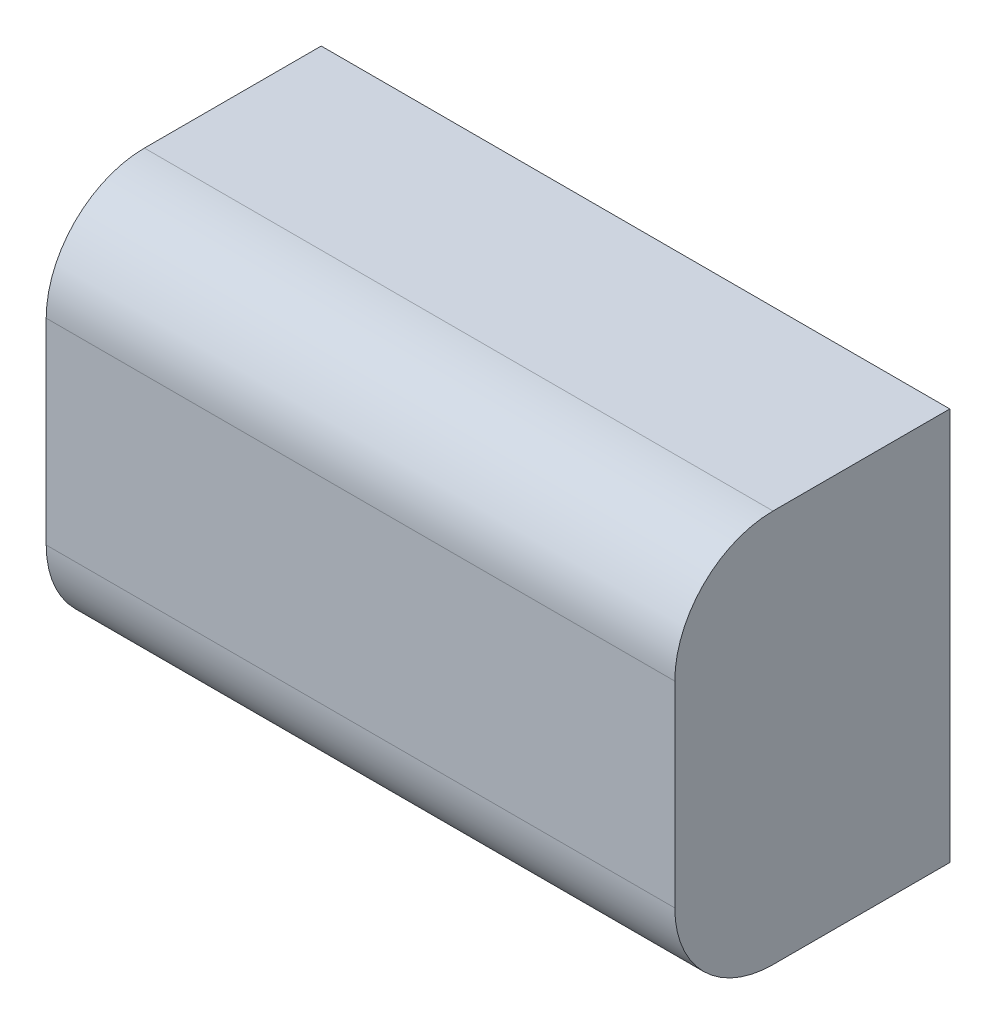
SolidWorks part; units mm, degrees
ref_plane "Front Plane" through (0, 0, 0) normal (0, 0, 1) x (1, 0, 0)
ref_plane "Top Plane" through (0, 0, 0) normal (0, 1, 0) x (1, 0, 0)
ref_plane "Right Plane" through (0, 0, 0) normal (1, 0, 0) x (0, 0, -1)
sketch "Sketch1" plane through (0, 0, 0) normal (0, 0, 1) x (1, 0, 0)
  line L1 (-101.6, 63.5) -> (101.6, 63.5)
  line L2 (-101.6, 63.5) -> (-101.6, -63.5)
  line L3 (-101.6, -63.5) -> (101.6, -63.5)
  line L4 (101.6, 63.5) -> (101.6, -63.5)
  line L5 (-101.6, 63.5) -> (101.6, -63.5) construction
  line L6 (-101.6, -63.5) -> (101.6, 63.5) construction
  point P0 (0, 0)
  point P13 (0, 0)
  dimension "D1" = 127
  dimension "D2" = 203.2
extrude "Boss-Extrude1" add sketch "Sketch1" along normal mid plane 88.9
fillet "Fillet1" radius 31.75 2 edges at (0, -63.5, 44.45) (0, 63.5, 44.45)
sketch "Sketch3" plane through (0, 0, -44.45) normal (0, 0, -1) x (-1, 0, 0)
  line L0 (-12.7, 0) -> (12.7, 0) construction
  circle A0 centre (-12.7, 0) radius 4.7625
  circle A1 centre (12.7, 0) radius 4.7625
  point P4 (0, 0)
  dimension "D1" = 9.525
  dimension "D2" = 25.4
extrude "Cut-Extrude1" cut sketch "Sketch3" against normal blind 25.4
